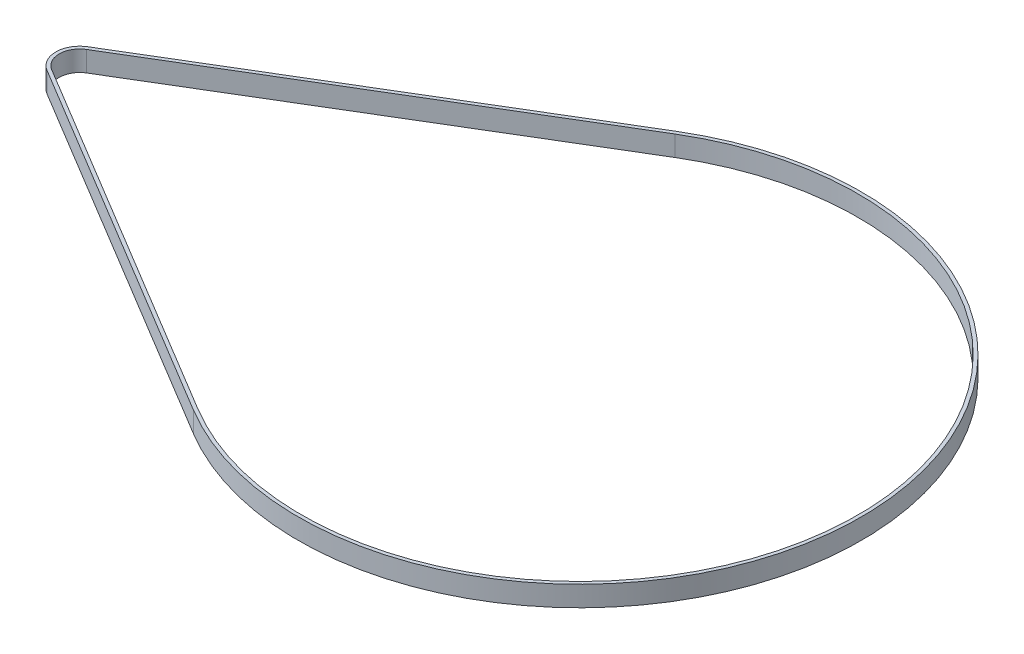
SolidWorks part; units mm, degrees
material "Rubber"
ref_plane "Front" through (0, 0, 0) normal (0, 0, 1) x (1, 0, 0)
ref_plane "Top" through (0, 0, 0) normal (0, 1, 0) x (1, 0, 0)
ref_plane "Right" through (0, 0, 0) normal (1, 0, 0) x (0, 0, -1)
sketch "Sketch1" plane through (0, 0, 0) normal (0, 1, 0) x (1, 0, 0)
  line L0 (-73.5331, 0) -> (73.5331, 0) construction
  line L1 (-76.6259, 5.1415) -> (31.3662, 70.1008) construction
  line L2 (-76.6259, -5.1415) -> (31.3662, -70.1008) construction
  line L3 (-77.1413, 5.9984) -> (30.8508, 70.9577)
  line L4 (-77.1413, -5.9984) -> (30.8508, -70.9577)
  line L5 (-76.6259, 5.1415) -> (31.3662, 70.1008)
  line L6 (31.3662, -70.1008) -> (-76.6259, -5.1415)
  arc A0 (31.3662, -70.1008) -> (31.3662, 70.1008) centre (73.5331, 0) ccw construction
  arc A1 (-76.6259, 5.1415) -> (-76.6259, -5.1415) centre (-73.5331, 0) ccw construction
  arc A2 (30.8508, -70.9577) -> (30.8508, 70.9577) centre (73.5331, 0) ccw
  arc A3 (-77.1413, 5.9984) -> (-77.1413, -5.9984) centre (-73.5331, 0) ccw
  arc A4 (-76.6259, -5.1415) -> (-76.6259, 5.1415) centre (-73.5331, 0) cw
  arc A5 (31.3662, -70.1008) -> (31.3662, 70.1008) centre (73.5331, 0) ccw
  point P2 (0, 0)
  dimension "D1" = 163.6113
  dimension "D2" = 12
  dimension "D3" = 610
  dimension "D4" = 1
extrude "Boss-Extrude1" add sketch "Sketch1" along normal blind 6 contours L4 A2 L3 A3
